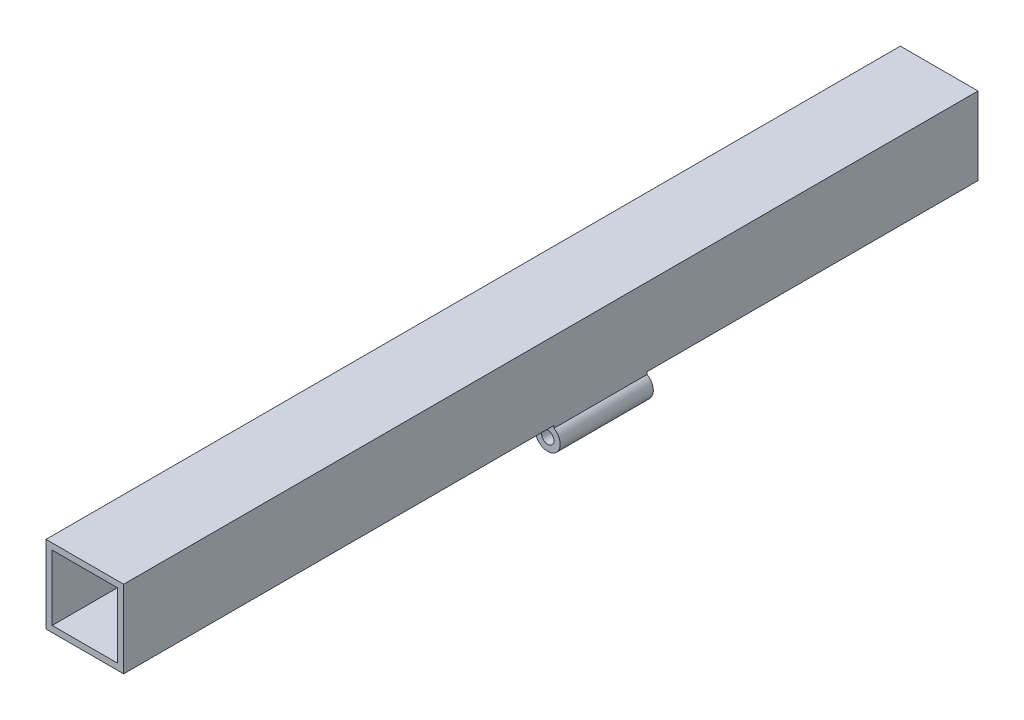
SolidWorks part; units mm, degrees
ref_plane "Front Plane" through (0, 0, 0) normal (0, 0, 1) x (1, 0, 0)
ref_plane "Top Plane" through (0, 0, 0) normal (0, 1, 0) x (1, 0, 0)
ref_plane "Right Plane" through (0, 0, 0) normal (1, 0, 0) x (0, 0, -1)
sketch "Sketch1" plane through (0, 0, 0) normal (0, 0, 1) x (1, 0, 0)
  line L1 (-12.5, -12.5) -> (12.5, -12.5)
  line L2 (-12.5, -12.5) -> (-12.5, 12.5)
  line L3 (-12.5, 12.5) -> (12.5, 12.5)
  line L4 (12.5, -12.5) -> (12.5, 12.5)
  line L5 (-12.5, -12.5) -> (12.5, 12.5) construction
  line L6 (-12.5, 12.5) -> (12.5, -12.5) construction
  line L7 (-10.5, 10.5) -> (10.5, 10.5)
  line L8 (-10.5, 10.5) -> (-10.5, -10.5)
  line L9 (-10.5, -10.5) -> (10.5, -10.5)
  line L10 (10.5, 10.5) -> (10.5, -10.5)
  line L11 (-10.5, 10.5) -> (10.5, -10.5) construction
  line L12 (-10.5, -10.5) -> (10.5, 10.5) construction
  point P0 (0, 0)
  point P6 (0, 0)
  dimension "D1" = 25
  dimension "D2" = 25
  dimension "D3" = 2
extrude "Boss-Extrude1" add sketch "Sketch1" along normal blind 275
ref_plane "Plane1" through (0, 0, 136.5) normal (0, 0, 1) x (1, 0, 0)
sketch "Sketch2" plane through (0, 0, 136.5) normal (0, 0, 1) x (1, 0, 0)
  line L0 (12.5, -12.5) -> (12.5, -13.2859)
  line L1 (8.5, -13.2859) -> (8.5, -12.5)
  line L2 (-12.5, -12.5) -> (12.5, -12.5) construction
  line L3 (8.5, -12.5) -> (12.5, -12.5)
  arc A0 (8.5, -13.2859) -> (12.5, -13.2859) centre (10.5, -16.75) ccw
  circle A1 centre (10.5, -16.75) radius 2
  dimension "D1" = 8
  dimension "D2" = 4
  dimension "D3" = 6.25
extrude "Boss-Extrude2" add sketch "Sketch2" against normal blind 30
